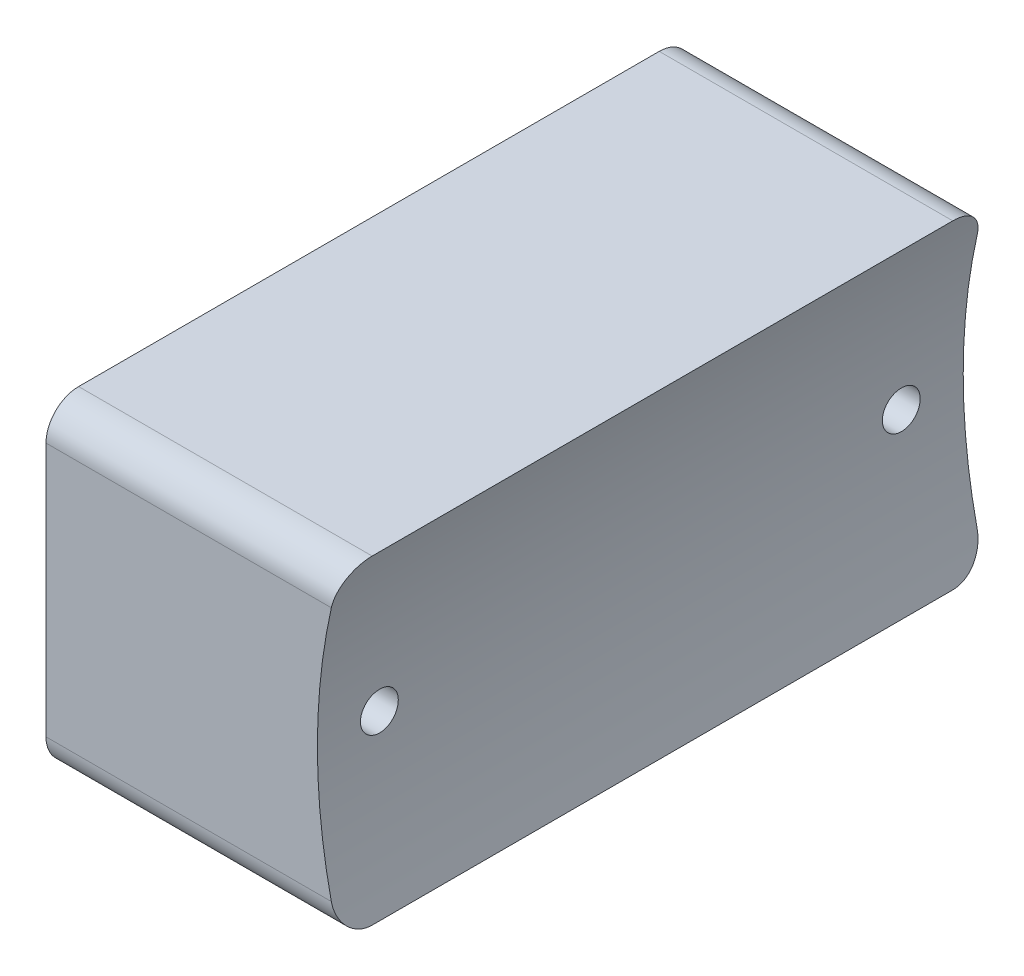
SolidWorks part; units mm, degrees
ref_plane "Спереди" through (0, 0, 0) normal (0, 0, 1) x (1, 0, 0)
ref_plane "Сверху" through (0, 0, 0) normal (0, 1, 0) x (1, 0, 0)
ref_plane "Справа" through (0, 0, 0) normal (1, 0, 0) x (0, 0, -1)
sketch "Эскиз1" plane through (0, 0, 0) normal (1, 0, 0) x (0, 0, -1)
  line L0 (-1050, 0) -> (48950, 0) construction
  line L1 (0, -1021.7777) -> (0, 48978.2223) construction
  line L2 (-24.75, -12.25) -> (24.75, -12.25)
  line L3 (-24.75, -12.25) -> (-24.75, 12.25)
  line L4 (-24.75, 12.25) -> (24.75, 12.25)
  line L5 (24.75, -12.25) -> (24.75, 12.25)
  line L6 (-24.75, -12.25) -> (24.75, 12.25) construction
  line L7 (-24.75, 12.25) -> (24.75, -12.25) construction
  point P3 (0, 0)
  point P10 (0, 0)
  point P11 (0, 0)
  point P13 (0, 0)
  point P21 (0, 0)
  dimension "D1" = 24.5
  dimension "D2" = 49.5
extrude "Бобышка-Вытянуть1" add sketch "Эскиз1" along normal blind 22.5
sketch "Эскиз2" plane through (0, 0, 0) normal (-1, 0, 0) x (0, 0, 1)
  line L1 (-24.75, -12.25) -> (-24.75, 12.25) construction
  line L2 (24.75, 12.25) -> (24.75, -12.25) construction
  line L3 (24.75, -12.25) -> (-24.75, -12.25) construction
  circle A0 centre (-20, -7.25) radius 2.5
  circle A1 centre (20, -7.25) radius 2.5
  point P12 (20.1343, 10.3169)
  dimension "D3" = 5
  dimension "D1" = 5
  dimension "D2" = 4.75
  dimension "D4" = 4.75
  dimension "D5" = 5
extrude "Вырез-Вытянуть1" cut sketch "Эскиз2" against normal blind 3
sketch "Эскиз3" plane through (0, 0, 0) normal (-1, 0, 0) x (0, 0, 1)
  line L0 (0, -1000) -> (0, 49000) construction
  line L2 (-7.6, 7.5) -> (7.6, 7.5)
  line L3 (-7.6, 7.5) -> (-7.6, 10)
  line L4 (-7.6, 10) -> (7.6, 10)
  line L5 (7.6, 7.5) -> (7.6, 10)
  line L6 (-7.6, 7.5) -> (7.6, 10) construction
  line L7 (-7.6, 10) -> (7.6, 7.5) construction
  line L8 (-24.75, 12.25) -> (24.75, 12.25) construction
  point P1 (0, 8.75)
  dimension "D1" = 15.2
  dimension "D2" = 2.5
  dimension "D3" = 2.25
extrude "Вырез-Вытянуть2" cut sketch "Эскиз3" against normal blind 8
sketch "Эскиз4" plane through (0, 0, -24.75) normal (0, 0, -1) x (-1, 0, 0)
  line L2 (-22.5, 12.25) -> (-22.5, -12.25)
  arc A0 (-38.4051, 35.7) -> (-38.4051, -35.7) centre (-65.8005, 0) cw construction
  arc A1 (-22.5, 12.25) -> (-22.5, -12.25) centre (-65.8005, 0) cw
  point P6 (-20, 12.4735)
  point P10 (0, 0)
  point P11 (0, 0)
  dimension "D1" = 71.4
  dimension "D2" = 45
extrude "Вырез-Вытянуть3" cut sketch "Эскиз4" against normal blind 50
sketch "Эскиз5" plane through (0, 0, 0) normal (1, 0, 0) x (0, 0, -1)
  line L0 (-1000, 0) -> (49000, 0) construction
  circle A0 centre (-20, 0) radius 1.45
  circle A1 centre (20, 0) radius 1.45
  dimension "D1" = 2.9
  dimension "D2" = 20
  dimension "D3" = 20
extrude "Вырез-Вытянуть4" cut sketch "Эскиз5" against normal blind 10 from offset 22.5
fillet "Скругление1" radius 2.5 4 edges at (11.25, -12.25, 24.75) (11.25, 12.25, 24.75) (11.25, -12.25, -24.75) (11.25, 12.25, -24.75)
